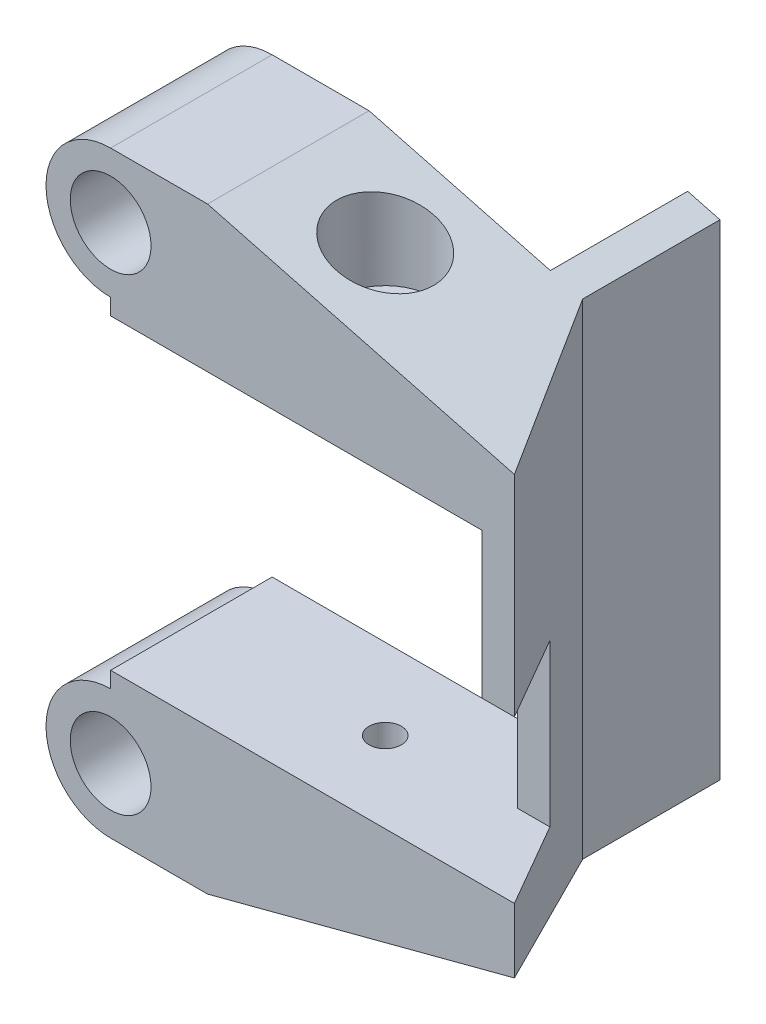
SolidWorks part; units mm, degrees
ref_plane "Alzado" through (0, 0, 0) normal (0, 0, 1) x (1, 0, 0)
ref_plane "Planta" through (0, 0, 0) normal (0, 1, 0) x (1, 0, 0)
ref_plane "Vista lateral" through (0, 0, 0) normal (1, 0, 0) x (0, 0, -1)
sketch "Croquis1" plane through (0, 0, 0) normal (0, 0, 1) x (1, 0, 0)
  line L5 (-106.2316, 22.7007) -> (-131.2316, 22.7007)
  line L6 (-131.2316, 22.7007) -> (-131.2316, 21.7007)
  line L7 (-106.2316, 22.7007) -> (-106.2316, 18.7007)
  line L8 (-106.2316, 18.7007) -> (-125.2316, 18.7007)
  line L9 (-125.2316, 18.7007) -> (-125.2316, 13.7007)
  line L10 (-125.2316, 13.7007) -> (-131.2316, 13.7007)
  circle A0 centre (-131.2316, 17.7007) radius 2.5
  arc A2 (-131.2316, 21.7007) -> (-131.2316, 13.7007) centre (-131.2316, 17.7007) ccw
  dimension "D1" = 4
  dimension "D2" = 5
  dimension "D3" = 6
  dimension "D4" = 5
  dimension "D5" = 25
  dimension "D6" = 5
extrude "Saliente-Extruir1" add sketch "Croquis1" along normal blind 10
sketch "Croquis2" plane through (0, 18.7007, 0) normal (0, -1, 0) x (1, 0, 0)
  line L1 (-106.2316, 0) -> (-106.2316, 10)
  line L2 (-106.2316, 10) -> (-112.0051, 0)
  line L4 (-112.0051, 0) -> (-106.2316, 0)
  line L5 (-125.2316, 10) -> (-125.2316, 0) construction
  line L6 (-106.2316, 10) -> (-106.2316, 0) construction
  circle A0 centre (-119.2316, 5) radius 1
  dimension "D1" = 6
  dimension "D2" = 30
  dimension "D3" = 0
extrude "Cortar-Extruir1" cut sketch "Croquis2" against normal up to vertex (4 mm away)
sketch "Croquis3" plane through (0, 18.7007, 0) normal (0, -1, 0) x (1, 0, 0)
  line L0 (-106.2316, 10) -> (-108.2316, 10)
  line L1 (-108.2316, 10) -> (-114.0051, 0)
  line L2 (-114.0051, 0) -> (-112.0051, 0)
  line L3 (-106.2316, 10) -> (-112.0051, 0)
  dimension "D1" = 2
  dimension "D2" = 2
extrude "Saliente-Extruir2" add sketch "Croquis3" against normal blind 13.5
sketch "Croquis4" plane through (0, 18.7007, 0) normal (0, -1, 0) x (1, 0, 0)
  circle A0 centre (-119.2316, 5) radius 3
extrude "Cortar-Extruir2" cut sketch "Croquis4" against normal blind 1
sketch "Croquis5" plane through (0, 0, 10) normal (0, 0, 1) x (1, 0, 0)
  line L0 (-106.2316, 18.7007) -> (-106.2316, 32.2007) construction
  line L1 (-108.2316, 22.7007) -> (-106.2316, 22.7007)
  line L2 (-108.2316, 22.7007) -> (-108.2316, 32.7007)
  line L3 (-108.2316, 32.7007) -> (-106.2316, 32.7007)
  line L4 (-106.2316, 22.7007) -> (-106.2316, 32.7007)
  dimension "D1" = 10
sketch "Croquis6" plane through (0, 18.7007, 0) normal (0, -1, 0) x (1, 0, 0)
  line L0 (-106.2316, 10) -> (-125.2316, 10)
  line L1 (-125.2316, 10) -> (-125.2316, 0)
  line L2 (-125.2316, 0) -> (-112.0051, 0)
  line L3 (-112.0051, 0) -> (-106.2316, 10)
  circle A0 centre (-119.2316, 5) radius 3
extrude "Saliente-Extruir3" add sketch "Croquis6" along normal up to vertex (5 mm away)
sketch "Croquis7" plane through (0, 0, 10) normal (0, 0, 1) x (1, 0, 0)
  line L0 (-106.2316, 18.7007) -> (-106.2316, 13.7007)
  line L1 (-106.2316, 13.7007) -> (-106.2316, 32.2007) construction
  line L2 (-106.2316, 13.7007) -> (-125.2316, 13.7007)
  line L3 (-131.2316, 13.7007) -> (-106.2316, 13.7007) construction
  line L4 (-125.2316, 13.7007) -> (-106.2316, 18.7007)
  line L5 (-108.2316, 22.7007) -> (-131.2316, 22.7007) construction
  dimension "D1" = 4
  dimension "D2" = 19
extrude "Cortar-Extruir3" cut sketch "Croquis7" against normal up to vertex (10 mm away)
sketch "Croquis8" plane through (0, 0, 0) normal (0, 0, -1) x (-1, 0, 0)
  line L0 (112.0051, 17.1813) -> (112.0051, 32.2007)
  line L1 (112.0051, 32.2007) -> (114.0051, 32.2007)
  line L2 (114.0051, 32.2007) -> (114.0051, 16.655)
  line L3 (112.0051, 17.1813) -> (125.2316, 13.7007) construction
  line L4 (114.0051, 16.655) -> (112.0051, 17.1813)
extrude "Saliente-Extruir4" add sketch "Croquis8" along normal blind 8.5
mirror "Simetría1" about plane through (0, 32.2007, 0) normal (0, -1, 0) of bodies 110
extrude "Cortar-Extruir4" cut sketch "Croquis5" along direction (-0.5, 0, -0.866) on the side against the normal blind 6
